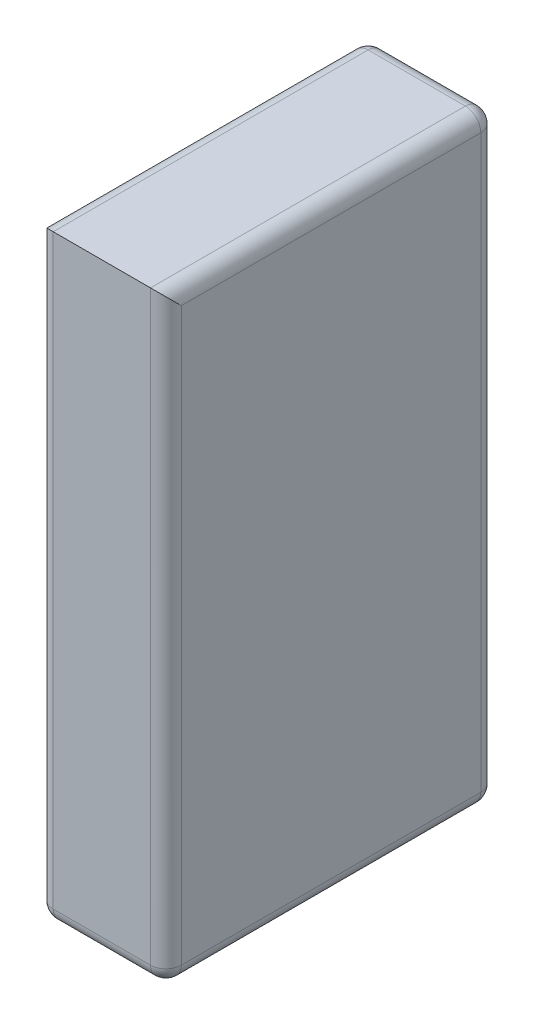
SolidWorks part; units mm, degrees
ref_plane "Front Plane" through (0, 0, 0) normal (1, 0, 0) x (0, 1, 0)
ref_plane "Top Plane" through (0, 0, 0) normal (0, 0, 1) x (0, 1, 0)
ref_plane "Right Plane" through (0, 0, 0) normal (0, 1, 0) x (-1, 0, 0)
sketch "Sketch1" plane through (0, 0, 0) normal (1, 0, 0) x (0, 1, 0)
  line L1 (0, 0) -> (78, 0)
  line L2 (0, 0) -> (0, 42.8)
  line L3 (0, 42.8) -> (78, 42.8)
  line L4 (78, 0) -> (78, 42.8)
  dimension "D1" = 42.8
  dimension "D2" = 78
extrude "Boss-Extrude1" add sketch "Sketch1" along normal blind 16.6
fillet "Fillet1" radius 2 11 edges at (0, 39, 0) (0, 78, 21.4) (0, 39, 42.8) (0, 0, 21.4) (16.6, 39, 42.8) (16.6, 78, 21.4) (16.6, 39, 0) (16.6, 0, 21.4) (8.3, 0, 0) (8.3, 78, 0) (8.3, 0, 42.8)
